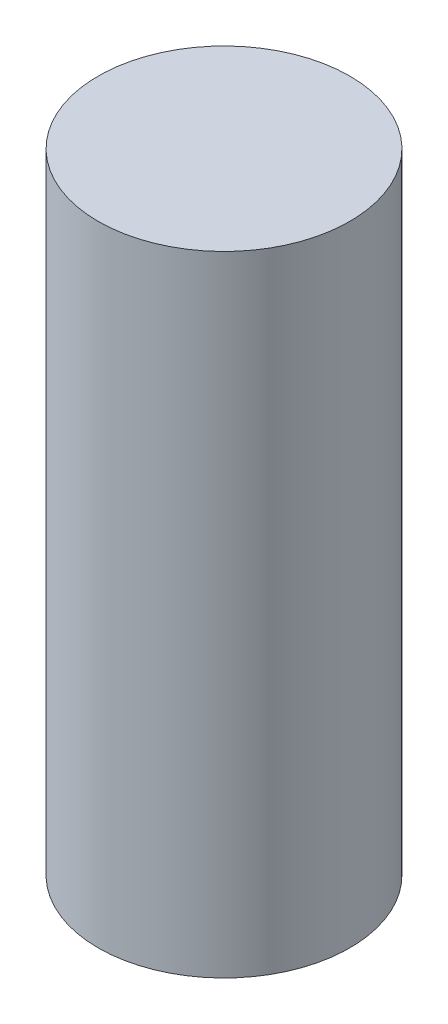
SolidWorks part; units mm, degrees
ref_plane "前视基准面" through (0, 0, 0) normal (0, 0, 1) x (1, 0, 0)
ref_plane "上视基准面" through (0, 0, 0) normal (0, 1, 0) x (1, 0, 0)
ref_plane "右视基准面" through (0, 0, 0) normal (1, 0, 0) x (0, 0, -1)
other "Configuration Table"
sketch "草图1" plane through (0, 0, 0) normal (0, 1, 0) x (1, 0, 0)
  circle A0 centre (0, 0) radius 7
extrude "凸台-拉伸2" add sketch "草图1" along normal blind 30 contours A0
sketch "草图4" plane through (0, 30, 0) normal (0, 1, 0) x (1, 0, 0)
  circle A1 centre (0, 0) radius 7
  circle A2 centre (0, 0) radius 7
  dimension "D1" = 0
extrude "切除-拉伸1" cut sketch "草图4" against normal blind 5
sketch "草图5" plane through (0, 25, 0) normal (0, 1, 0) x (1, 0, 0)
  circle A1 centre (0, 0) radius 7
  circle A2 centre (0, 0) radius 7
  dimension "D1" = 0
extrude "凸台-拉伸3" add sketch "草图5" along normal blind 10
